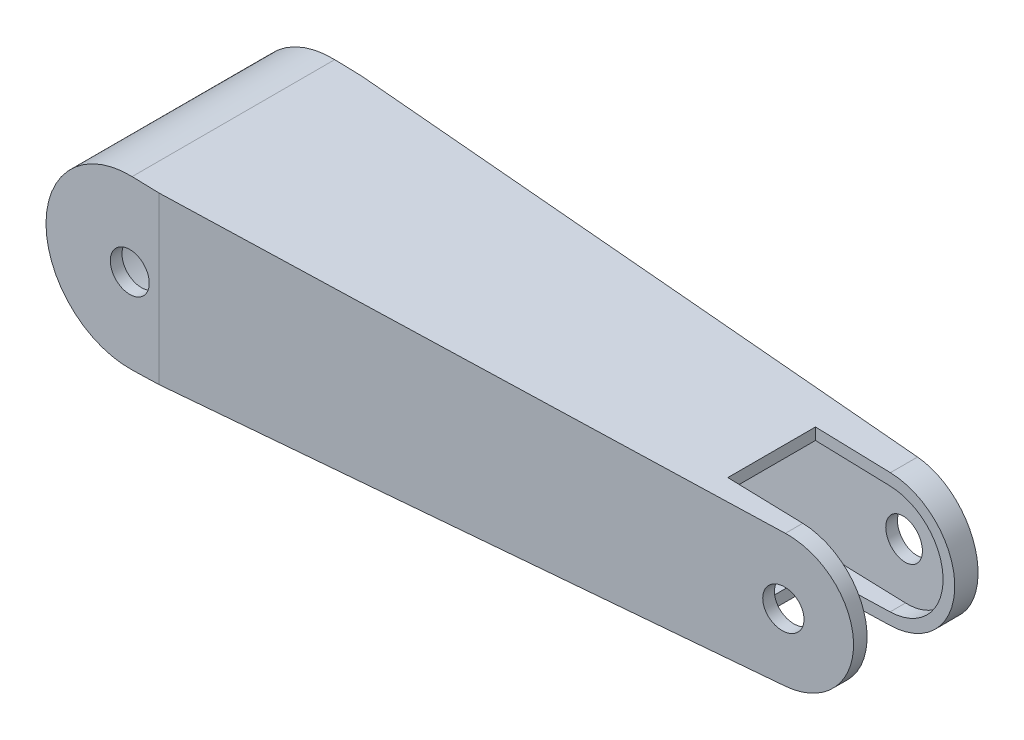
SolidWorks part; units mm, degrees
ref_plane "Plan de face" through (0, 0, 0) normal (0, 0, 1) x (1, 0, 0)
ref_plane "Plan de dessus" through (0, 0, 0) normal (0, 1, 0) x (1, 0, 0)
ref_plane "Plan de droite" through (0, 0, 0) normal (1, 0, 0) x (0, 0, -1)
sketch "Esquisse2" plane through (0, 0, 0) normal (0, 0, 1) x (1, 0, 0)
  line L0 (-160.2273, 0) -> (254.66, 0) construction
  line L1 (-105.5703, 42.9827) -> (211.6745, 33.9863)
  line L2 (-105.5703, -42.9827) -> (211.6745, -33.9863)
  arc A0 (-105.5703, 42.9827) -> (-105.5703, -42.9827) centre (-106.7892, 0) ccw
  arc A1 (211.6745, -33.9863) -> (211.6745, 33.9863) centre (210.7108, 0) ccw
  dimension "D2" = 86
  dimension "D3" = 68
  dimension "D1" = 317.5
extrude "Extrusion1" add sketch "Esquisse2" along normal blind 200
sketch "Esquisse4" plane through (0, 0, 0) normal (0, 1, 0) x (1, 0, 0)
  line L0 (-324.7722, -100) -> (337.3509, -100) construction
  line L1 (-158.7892, -152) -> (-158.7892, -48)
  line L2 (-158.7892, -48) -> (-91.7892, -48)
  line L3 (-91.7892, -48) -> (311.2108, -72)
  line L4 (311.2108, -72) -> (311.2108, -128)
  line L5 (-106.7892, -200) -> (-106.7892, 0) construction
  line L6 (211.6745, -200) -> (-105.5703, -200) construction
  line L7 (-91.7892, -152) -> (311.2108, -128)
  line L8 (-158.7892, -152) -> (-91.7892, -152)
  point P12 (311.2108, -100)
  point P14 (-158.7892, -100)
  dimension "D1" = 52
  dimension "D2" = 28
  dimension "D3" = 67
  dimension "D4" = 52
  dimension "D5" = 470
  dimension "D6" = 100
extrude "Enlèv. mat.-Extru.1" cut sketch "Esquisse4" against normal through all and the other way through all flip side to cut
shell "Coque5" thickness 6
sketch "Esquisse5" plane through (0, 0, 0) normal (0, 1, 0) x (1, 0, 0)
  line L0 (-106.7892, -152) -> (-106.7892, -48) construction
  line L1 (173.2108, -80) -> (273.2108, -80)
  line L2 (173.2108, -80) -> (173.2108, -125)
  line L3 (173.2108, -125) -> (273.2108, -125)
  line L4 (273.2108, -80) -> (273.2108, -125)
  line L5 (-105.5703, -48) -> (-149.7892, -48) construction
  dimension "D1" = 280
  dimension "D2" = 100
  dimension "D3" = 45
  dimension "D4" = 32
extrude "Enlèv. mat.-Extru.2" cut sketch "Esquisse5" against normal through all and the other way through all
sketch "Esquisse6" plane through (0, 0, 152) normal (0, 0, 1) x (1, 0, 0)
  circle A0 centre (210.7108, 0) radius 10
  arc A1 (211.6745, -33.9863) -> (211.6745, 33.9863) centre (210.7108, 0) ccw construction
  dimension "D1" = 20
extrude "Enlèv. mat.-Extru.3" cut sketch "Esquisse6" against normal through all
sketch "Esquisse7" plane through (0, 0, 152) normal (0, 0, 1) x (1, 0, 0)
  circle A0 centre (-106.7892, 0) radius 10
  arc A1 (-105.5703, 42.9827) -> (-105.5703, -42.9827) centre (-106.7892, 0) ccw construction
  dimension "D1" = 20
extrude "Enlèv. mat.-Extru.4" cut sketch "Esquisse7" against normal through all
ref_plane "Plan1" through (0, 0, 100) normal (0, 0, -1) x (-1, 0, 0)
